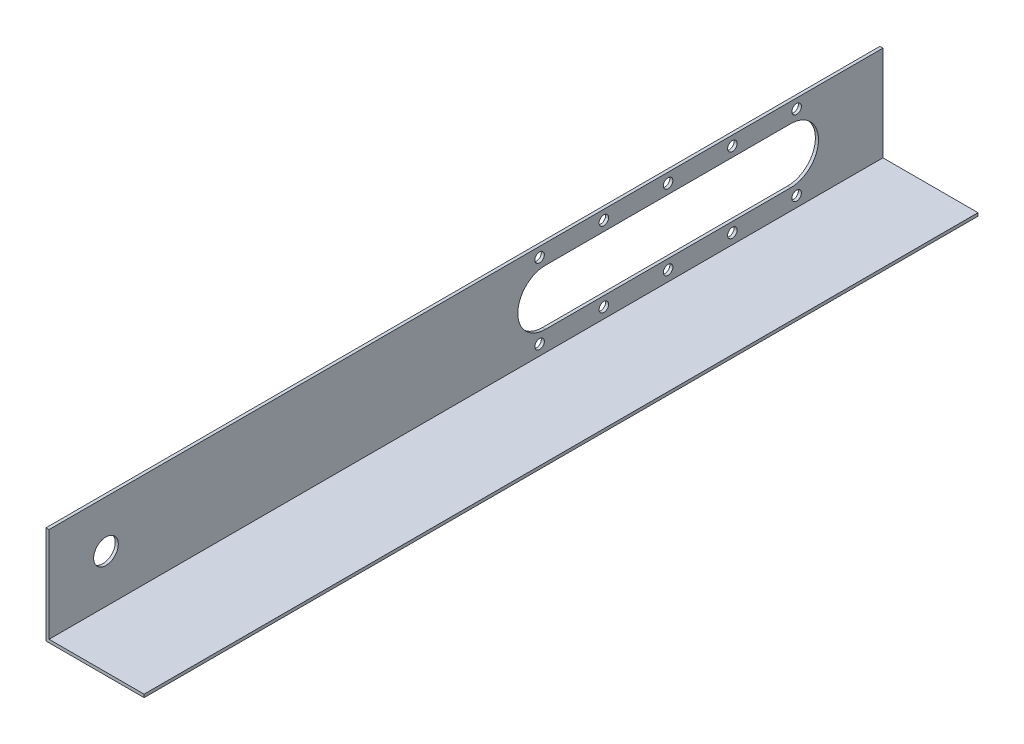
SolidWorks part; units mm, degrees
ref_plane "Front Plane" through (0, 0, 0) normal (0, 0, 1) x (1, 0, 0)
ref_plane "Top Plane" through (0, 0, 0) normal (0, 1, 0) x (1, 0, 0)
ref_plane "Right Plane" through (0, 0, 0) normal (1, 0, 0) x (0, 0, -1)
sketch "Sketch3" plane through (0, 0, 0) normal (0, 0, 1) x (1, 0, 0)
  line L0 (0, 0) -> (0, 49.2125)
  line L1 (0, 49.2125) -> (-1.5875, 49.2125)
  line L2 (-1.5875, 49.2125) -> (-1.5875, -1.5875)
  line L3 (-1.5875, -1.5875) -> (49.2125, -1.5875)
  line L4 (49.2125, -1.5875) -> (49.2125, 0)
  line L5 (49.2125, 0) -> (0, 0)
  dimension "D1" = 1.5875
  dimension "D2" = 1.5875
  dimension "D3" = 50.8
  dimension "D4" = 50.8
extrude "Boss-Extrude2" add sketch "Sketch3" along normal blind 431.8
sketch "Sketch6" plane through (0, 0, 0) normal (1, 0, 0) x (0, 0, -1)
  line L0 (-174.752, 24.8285) -> (-47.752, 24.8285) construction
  line L1 (-174.752, 39.1795) -> (-47.752, 39.1795)
  line L2 (-174.752, 10.4775) -> (-47.752, 10.4775)
  line L4 (0, 0) -> (0, 49.2125) construction
  line L5 (-431.8, 49.2125) -> (0, 49.2125) construction
  arc A0 (-174.752, 39.1795) -> (-174.752, 10.4775) centre (-174.752, 24.8285) ccw
  arc A1 (-47.752, 10.4775) -> (-47.752, 39.1795) centre (-47.752, 24.8285) ccw
  point P2 (-111.252, 24.8285)
  dimension "D3" = 47.752
  dimension "D1" = 28.702
  dimension "D2" = 127
  dimension "D4" = 24.384
extrude "Cut-Extrude3" cut sketch "Sketch6" against normal blind 127
sketch "Sketch7" plane through (0, 0, 0) normal (1, 0, 0) x (0, 0, -1)
  line L0 (-431.8, 0) -> (-431.8, 49.2125) construction
  line L1 (-431.8, 49.2125) -> (0, 49.2125) construction
  circle A0 centre (-402.336, 24.7736) radius 6.3881
  dimension "D1" = 12.7762
  dimension "D3" = 24.4389
  dimension "D2" = 29.464
extrude "Cut-Extrude4" cut sketch "Sketch7" against normal through all
sketch "Sketch12" plane through (0, 0, 0) normal (1, 0, 0) x (0, 0, -1)
  line L0 (-47.752, 39.1795) -> (-174.752, 39.1795) construction
  line L1 (-174.752, 10.4775) -> (-47.752, 10.4775) construction
  arc A0 (-174.752, 39.1795) -> (-174.752, 10.4775) centre (-174.752, 24.8285) ccw construction
  point P0 (-111.252, 44.2595)
  point P1 (-177.8, 44.2595)
  point P4 (-111.252, 39.1795)
  point P6 (-111.252, 5.3975)
  point P7 (-177.8, 44.2595)
  point P8 (-177.8, 5.3975)
  point P10 (-177.8, 5.3975)
  point P12 (-144.526, 44.2595)
  point P13 (-144.526, 44.2595)
  point P14 (-144.526, 5.3975)
  point P15 (-144.526, 5.3975)
  point P16 (-77.978, 44.2595)
  point P17 (-44.704, 44.2595)
  point P18 (-77.978, 5.3975)
  point P21 (-44.704, 5.3975)
  dimension "D1" = 5.08
  dimension "D2" = 63.5
  dimension "D3" = 33.274
  dimension "D4" = 33.274
  dimension "D5" = 33.274
  dimension "D6" = 33.274
  dimension "D7" = 63.5
  dimension "D8" = 5.08
  dimension "D9" = 33.274
  dimension "D10" = 33.274
  dimension "D11" = 33.274
  dimension "D12" = 33.274
  dimension "D13" = 33.274
  dimension "D14" = 33.274
  dimension "D15" = 33.274
  dimension "D16" = 33.274
hole_wizard "#10 (0.1935) Diameter Hole3" positions "Sketch13" profile "Sketch14" hole size "#10" standard "ANSI Inch" end condition through all
sketch "Sketch13" plane through (0, 0, 0) normal (1, 0, 0) x (0, 0, -1)
  point P0 (-177.8, 44.2595)
  point P3 (-144.526, 44.2595)
  point P6 (-111.252, 44.2595)
  point P9 (-144.526, 44.2595)
  point P12 (-177.8, 44.2595)
  point P15 (-177.8, 5.3975)
  point P18 (-144.526, 5.3975)
  point P21 (-111.252, 5.3975)
  point P24 (-144.526, 5.3975)
  point P27 (-177.8, 5.3975)
  point P31 (-77.978, 44.2595)
  point P34 (-44.704, 44.2595)
  point P37 (-44.704, 5.3975)
  point P40 (-77.978, 5.3975)
sketch "Sketch14" plane through (0, 44.2595, 177.8) normal (0, 1, 0) x (0, 0, -1)
  line L0 (0, 0) -> (0, 1.5875)
  line L1 (0, 1.5875) -> (2.4574, 1.5875)
  line L2 (2.4574, 1.5875) -> (2.4574, 0)
  line L5 (2.4574, 0) -> (0, 0)
  line L11 (0, -6.35) -> (0, 107.95) construction
  dimension "Thru Hole Dia." = 4.9149
  dimension "Thru Hole Depth" = 1.5875
